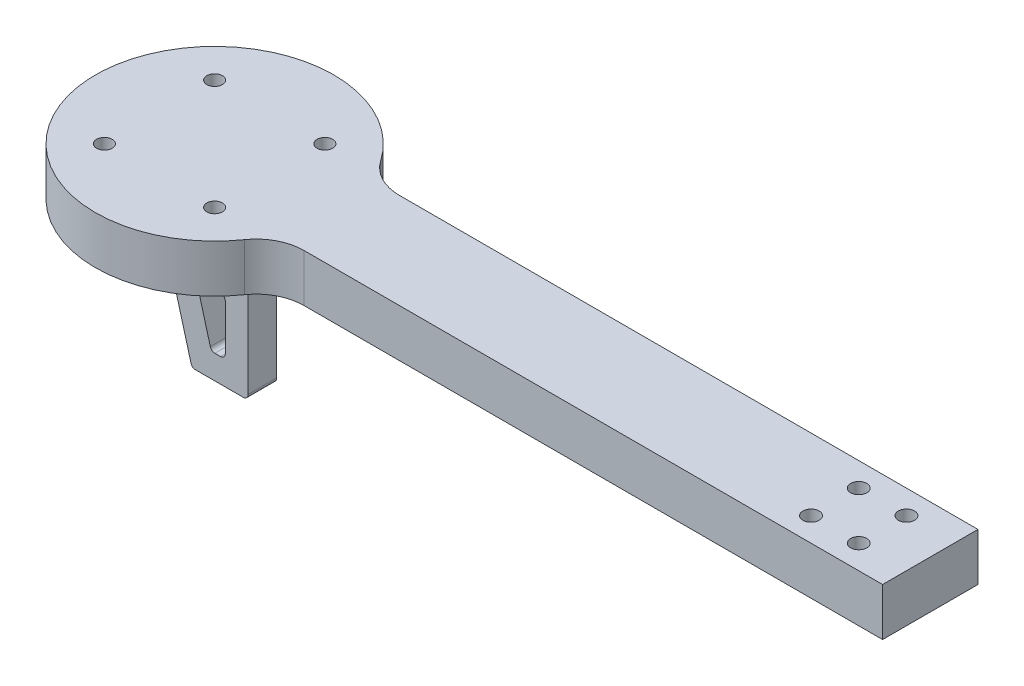
SolidWorks part; units mm, degrees
material "PEI"
ref_plane "Front Plane" through (0, 0, 0) normal (0, 0, 1) x (1, 0, 0)
ref_plane "Top Plane" through (0, 0, 0) normal (0, 1, 0) x (1, 0, 0)
ref_plane "Right Plane" through (0, 0, 0) normal (1, 0, 0) x (0, 0, -1)
sketch "Sketch1" plane through (0, 0, 0) normal (0, 1, 0) x (1, 0, 0)
  line L0 (-75, -10) -> (75, -10)
  line L1 (-75, -10) -> (-75, 10)
  line L2 (-75, 10) -> (75, 10)
  line L3 (75, -10) -> (75, 10)
  line L4 (-75, -10) -> (75, 10) construction
  line L5 (-75, 10) -> (75, -10) construction
  circle A0 centre (-75, 0) radius 25
  circle A1 centre (-75, 0) radius 16.3375 construction
  circle A2 centre (-86.5524, 11.5524) radius 1.635
  circle A3 centre (-63.4476, 11.5524) radius 1.635
  circle A4 centre (-75, 0) radius 16.3375 construction
  circle A5 centre (-63.4476, -11.5524) radius 1.635
  circle A6 centre (-75, 0) radius 16.3375 construction
  circle A7 centre (-86.5524, -11.5524) radius 1.635
  circle A8 centre (-75, 0) radius 16.3375 construction
  point P0 (0, 0)
  point P23 (-75, 0)
  dimension "D3" = 50
  dimension "D4" = 32.675
  dimension "D5" = 3.27
  dimension "D1" = 150
  dimension "D2" = 20
  dimension "D6" = 4
extrude "Boss-Extrude1" add sketch "Sketch1" along normal blind 10 contours A0 L0 L3 L2 | L2 A0 L0 L1 A7 A5 A2 | L0 A0 L2 L1 A3
fillet "Fillet1" radius 10 2 edges at (-52.0871, 5, -10) (-52.0871, 5, 10)
hole_wizard "M3 Clearance Hole1" positions "Sketch2" profile "Sketch3" hole size "M3" standard "ANSI Metric" end condition through all
sketch "Sketch2" plane through (0, 10, 0) normal (0, 1, 0) x (1, 0, 0)
  line L0 (75, -10) -> (75, 10) construction
  point P0 (65, 5)
  point P2 (65, -5)
  point P16 (55, 5)
  point P20 (55, -5)
  dimension "D1" = 10
  dimension "D2" = 10
  dimension "D3" = 5
  dimension "D4" = 10
sketch "Sketch3" plane through (65, 10, -5) normal (1, 0, 0) x (0, 0, 1)
  line L0 (0, 0) -> (0, 10)
  line L1 (0, 10) -> (1.7, 10)
  line L2 (1.7, 10) -> (1.7, 0)
  line L5 (1.7, 0) -> (0, 0)
  line L11 (0, -6.35) -> (0, 107.95) construction
  dimension "Thru Hole Dia." = 3.4
  dimension "Thru Hole Depth" = 10
sketch "Sketch4" plane through (0, 0, 0) normal (0, 0, 1) x (1, 0, 0)
  line L11 (-85, 0) -> (-65, 0)
  line L28 (-65, 0) -> (-64.9977, -29)
  line L32 (-76.9643, -29.2648) -> (-85, 0)
  line L33 (-65.9973, -30.0293) -> (-76.2403, -30.0294)
  line L34 (-69.7597, -14.4733) -> (-69.7597, -24)
  line L35 (-77.4498, -7.7381) -> (-77.8544, -6.2648)
  line L36 (-72.9118, -24.2648) -> (-75.5277, -14.7381)
  line L37 (-76.8901, -5) -> (-70.7597, -5)
  line L38 (-69.7597, -6) -> (-69.7597, -7.4733)
  line L39 (-76.4855, -8.4733) -> (-70.7597, -8.4733)
  line L40 (-74.5634, -13.4733) -> (-70.7597, -13.4733)
  line L41 (-70.7597, -25) -> (-71.9475, -25)
  arc A20 (-76.8901, -5) -> (-77.8544, -6.2648) centre (-76.8901, -6) ccw
  arc A21 (-76.4855, -8.4733) -> (-77.4498, -7.7381) centre (-76.4855, -7.4733) cw
  arc A22 (-75.5277, -14.7381) -> (-74.5634, -13.4733) centre (-74.5634, -14.4733) cw
  arc A23 (-70.7597, -5) -> (-69.7597, -6) centre (-70.7597, -6) cw
  arc A24 (-76.2403, -30.0294) -> (-76.9643, -29.2648) centre (-75.985, -29.0626) cw
  arc A25 (-69.7597, -7.4733) -> (-70.7597, -8.4733) centre (-70.7597, -7.4733) cw
  arc A26 (-70.7597, -25) -> (-69.7597, -24) centre (-70.7597, -24) ccw
  arc A27 (-72.9118, -24.2648) -> (-71.9475, -25) centre (-71.9475, -24) ccw
  arc A28 (-69.7597, -14.4733) -> (-70.7597, -13.4733) centre (-70.7597, -14.4733) ccw
  arc A29 (-64.9977, -29) -> (-65.9973, -30.0293) centre (-65.9973, -29.0293) cw
  dimension "D1" = 1
  dimension "D3" = 29
  dimension "D4" = 20
extrude "Boss-Extrude2" add sketch "Sketch4" along normal mid plane 6
